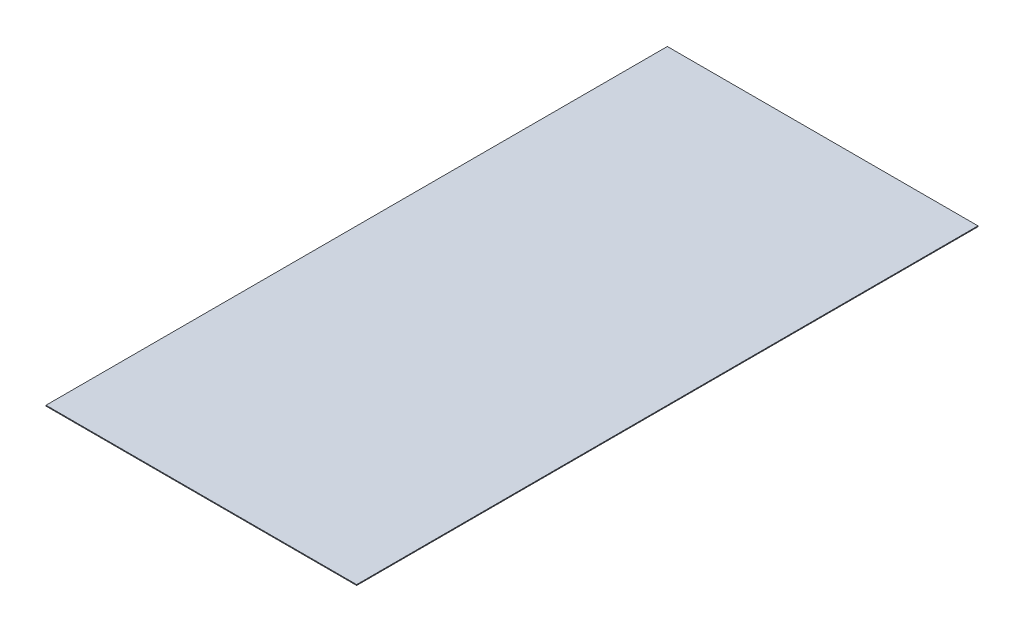
SolidWorks part; units mm, degrees
material "ASTM A36 Acero"
ref_plane "Alzado" through (0, 0, 0) normal (0, 0, 1) x (1, 0, 0)
ref_plane "Planta" through (0, 0, 0) normal (0, 1, 0) x (1, 0, 0)
ref_plane "Vista lateral" through (0, 0, 0) normal (1, 0, 0) x (0, 0, -1)
sketch "Croquis1" plane through (0, 0, 0) normal (0, 1, 0) x (1, 0, 0)
  line L1 (-609.6, -1219.2) -> (609.6, -1219.2)
  line L2 (-609.6, -1219.2) -> (-609.6, 1219.2)
  line L3 (-609.6, 1219.2) -> (609.6, 1219.2)
  line L4 (609.6, -1219.2) -> (609.6, 1219.2)
  line L5 (-609.6, -1219.2) -> (609.6, 1219.2) construction
  line L6 (-609.6, 1219.2) -> (609.6, -1219.2) construction
  point P0 (0, 0)
  dimension "D1" = 2438.4
  dimension "D2" = 1219.2
extrude "Saliente-Extruir1" add sketch "Croquis1" along normal blind 3.2
